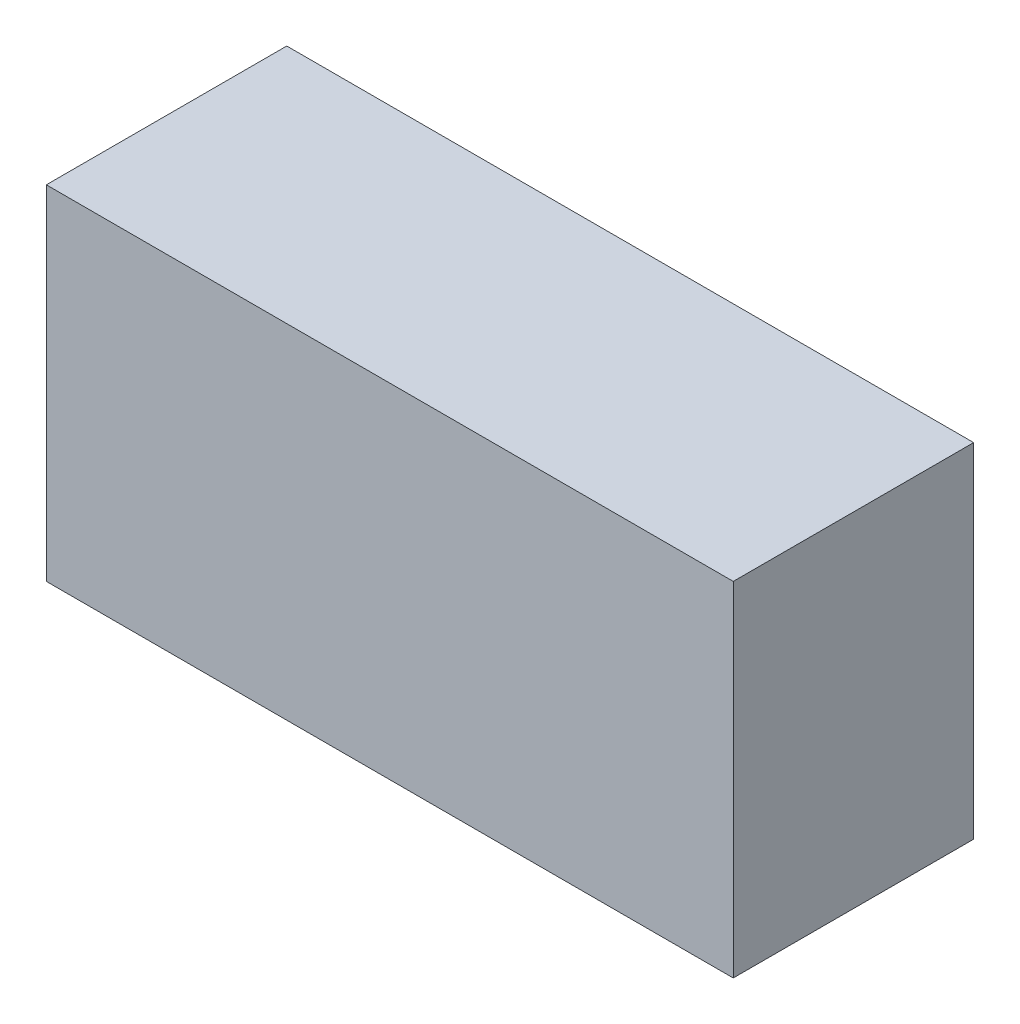
SolidWorks part; units mm, degrees
ref_plane "前视基准面" through (0, 0, 0) normal (0, 0, 1) x (1, 0, 0)
ref_plane "上视基准面" through (0, 0, 0) normal (0, 1, 0) x (1, 0, 0)
ref_plane "右视基准面" through (0, 0, 0) normal (1, 0, 0) x (0, 0, -1)
sketch "草图1" plane through (0, 0, 0) normal (0, 0, 1) x (1, 0, 0)
  line L1 (-100, 50) -> (100, 50)
  line L2 (-100, 50) -> (-100, -50)
  line L3 (-100, -50) -> (100, -50)
  line L4 (100, 50) -> (100, -50)
  line L5 (-100, 50) -> (100, -50) construction
  line L6 (-100, -50) -> (100, 50) construction
  point P0 (0, 0)
  dimension "D1" = 100
  dimension "D2" = 200
extrude "凸台-拉伸1" add sketch "草图1" along normal blind 70
sketch "草图3" plane through (0, 0, 0) normal (0, 0, -1) x (-1, 0, 0)
  circle A0 centre (0, 0) radius 25
  dimension "D1" = 50
extrude "凸台-拉伸2" add sketch "草图3" along normal blind 20 contours A0
